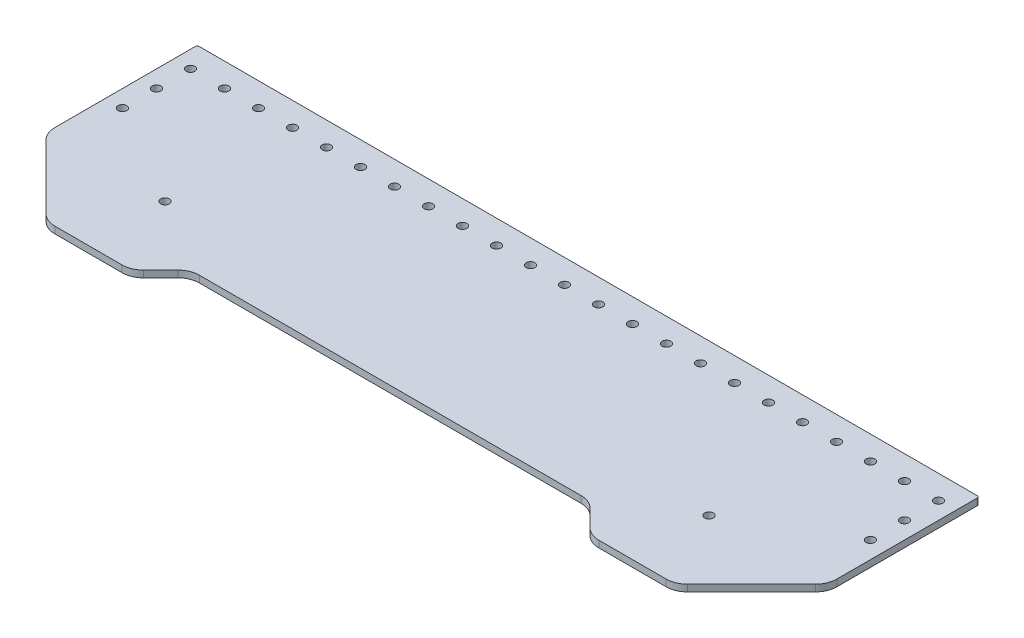
SolidWorks part; units mm, degrees
ref_plane "Front Plane" through (0, 0, 0) normal (0, 0, 1) x (1, 0, 0)
ref_plane "Top Plane" through (0, 0, 0) normal (0, 1, 0) x (1, 0, 0)
ref_plane "Right Plane" through (0, 0, 0) normal (1, 0, 0) x (0, 0, -1)
sketch "Sketch3" plane through (0, 0, 0) normal (0, 1, 0) x (1, 0, 0)
  line L0 (0, 0) -> (50000, 0) construction
  line L1 (184, -59.5875) -> (-184, -59.5875) construction
  line L2 (184, -59.5875) -> (184, 59.5875) construction
  line L3 (184, 59.5875) -> (-184, 59.5875) construction
  line L4 (-184, -59.5875) -> (-184, 59.5875) construction
  line L5 (184, -59.5875) -> (-184, 59.5875) construction
  line L6 (184, 59.5875) -> (-184, -59.5875) construction
  line L7 (0, 0) -> (0, -50000) construction
  line L8 (-141.9903, -11.5875) -> (49858.0097, -11.5875) construction
  line L9 (-130.2701, 7.3771) -> (-33.4655, 18.9646) construction
  line L10 (-128, -11.5875) -> (-31.1955, 0) construction
  line L11 (-125.7299, -30.5521) -> (-28.9254, -18.9646) construction
  line L12 (-49.1677, -33.5875) -> (49950.8323, -33.5875) construction
  line L13 (-47.419, -47.5875) -> (-50047.419, -47.5875) construction
  line L14 (-184, -11.5875) -> (-148, -47.5875)
  line L15 (-128, -11.5875) -> (-128, -50011.5875) construction
  line L16 (-148, -47.5875) -> (-108, -47.5875)
  line L17 (-94, -33.5875) -> (-108, -47.5875)
  line L18 (-94, -33.5875) -> (94, -33.5875)
  line L19 (-184, -11.5875) -> (-184, 59.5875)
  line L20 (-184, 59.5875) -> (184, 59.5875)
  line L21 (184, -11.5875) -> (184, 59.5875)
  line L22 (184, -11.5875) -> (148, -47.5875)
  line L23 (148, -47.5875) -> (108, -47.5875)
  line L24 (94, -33.5875) -> (108, -47.5875)
  line L26 (-15.1955, -16) -> (-47.1955, -16) construction
  line L27 (-15.1955, -16) -> (-15.1955, 16) construction
  line L28 (-15.1955, 16) -> (-47.1955, 16) construction
  line L29 (-47.1955, -16) -> (-47.1955, 16) construction
  line L30 (-15.1955, -16) -> (-47.1955, 16) construction
  line L31 (-15.1955, 16) -> (-47.1955, -16) construction
  line L32 (-9.1955, -22) -> (-53.1955, -22) construction
  line L33 (-9.1955, -22) -> (-9.1955, 22) construction
  line L34 (-9.1955, 22) -> (-53.1955, 22) construction
  line L35 (-53.1955, -22) -> (-53.1955, 22) construction
  line L36 (-9.1955, -22) -> (-53.1955, 22) construction
  line L37 (-9.1955, 22) -> (-53.1955, -22) construction
  circle A0 centre (-128, -11.5875) radius 48 construction
  circle A1 centre (-128, -11.5875) radius 19.1 construction
  circle A2 centre (-31.1955, 0) radius 19.1 construction
  arc A3 (-33.4655, 18.9646) -> (-28.9254, -18.9646) centre (-31.1955, 0) cw construction
  arc A4 (-130.2701, 7.3771) -> (-125.7299, -30.5521) centre (-128, -11.5875) ccw construction
  circle A5 centre (-128, -11.5875) radius 2.05
  circle A6 centre (-31.1955, 0) radius 2.05 construction
  circle A7 centre (128, -11.5875) radius 2.05
  circle A8 centre (31.1955, 0) radius 2.05 construction
  circle A9 centre (-53.1955, 22) radius 2.05 construction
  circle A10 centre (-53.1955, -22) radius 2.05 construction
  circle A11 centre (53.1955, 22) radius 2.05 construction
  circle A12 centre (53.1955, -22) radius 2.05 construction
  point P0 (0, 0)
  point P36 (0, 59.5875)
  point P40 (0, -33.5875)
  dimension "D4" = 96
  dimension "D6" = 38.2
  dimension "D12" = 4.1
  dimension "D1" = 368
  dimension "D2" = 119.175
  dimension "D3" = 48
  dimension "D5" = 56
  dimension "D8" = 26
  dimension "D9" = 12
  dimension "D10" = 45
  dimension "D11" = 45
  dimension "D13" = 32
  dimension "D14" = 44
extrude "Boss-Extrude2" add sketch "Sketch3" along normal blind 3.175
fillet "Fillet1" radius 10 8 edges at (184, 1.5875, 11.5875) (148, 1.5875, 47.5875) (108, 1.5875, 47.5875) (94, 1.5875, 33.5875) (-94, 1.5875, 33.5875) (-108, 1.5875, 47.5875) (-148, 1.5875, 47.5875) (-184, 1.5875, 11.5875)
fillet "Fillet2" radius 1 2 edges at (184, 1.5875, -59.5875) (-184, 1.5875, -59.5875)
sketch "Sketch5" plane through (0, 3.175, 0) normal (0, 1, 0) x (1, 0, 0)
  line L0 (0, 0) -> (0, -50000) construction
  circle A0 centre (-128, -11.5875) radius 48
  circle A1 centre (128, -11.5875) radius 48
  dimension "D1" = 96
sketch "Sketch6" plane through (0, 3.175, 0) normal (0, 1, 0) x (1, 0, 0)
  line L0 (0, 0) -> (0, -50000) construction
  line L2 (0, 0) -> (50000, 0) construction
  line L3 (21.2444, 56.4125) -> (50021.2444, 56.4125) construction
  line L4 (21.9898, 48.4125) -> (50021.9898, 48.4125) construction
  line L5 (183, 59.5875) -> (-183, 59.5875) construction
  line L6 (-176, 42.191) -> (-176, -49957.809) construction
  line L7 (-184, 58.5875) -> (-184, -7.4454) construction
  line L8 (-176, 48.4125) -> (-160, 48.4125) construction
  line L9 (-176, 48.4125) -> (-176.014, 32.4125) construction
  circle A0 centre (-176, 48.4125) radius 2.05
  circle A1 centre (-160, 48.4125) radius 2.05
  circle A2 centre (-144, 48.4125) radius 2.05
  circle A3 centre (-128, 48.4125) radius 2.05
  circle A4 centre (-112, 48.4125) radius 2.05
  circle A5 centre (-96, 48.4125) radius 2.05
  circle A6 centre (-80, 48.4125) radius 2.05
  circle A7 centre (-64, 48.4125) radius 2.05
  circle A8 centre (-48, 48.4125) radius 2.05
  circle A9 centre (-32, 48.4125) radius 2.05
  circle A10 centre (-16, 48.4125) radius 2.05
  circle A11 centre (0, 48.4125) radius 2.05
  circle A12 centre (16, 48.4125) radius 2.05
  circle A13 centre (32, 48.4125) radius 2.05
  circle A14 centre (48, 48.4125) radius 2.05
  circle A15 centre (64, 48.4125) radius 2.05
  circle A16 centre (80, 48.4125) radius 2.05
  circle A17 centre (96, 48.4125) radius 2.05
  circle A18 centre (112, 48.4125) radius 2.05
  circle A19 centre (128, 48.4125) radius 2.05
  circle A20 centre (144, 48.4125) radius 2.05
  circle A21 centre (160, 48.4125) radius 2.05
  circle A22 centre (176, 48.4125) radius 2.05
  circle A23 centre (-160.014, 32.4125) radius 2.05 construction
  circle A24 centre (-144.014, 32.4125) radius 2.05 construction
  circle A25 centre (-128.014, 32.4125) radius 2.05 construction
  circle A26 centre (-112.014, 32.4125) radius 2.05 construction
  circle A27 centre (-96.014, 32.4125) radius 2.05 construction
  circle A28 centre (-80.014, 32.4125) radius 2.05 construction
  circle A29 centre (-64.014, 32.4125) radius 2.05 construction
  circle A30 centre (-48.014, 32.4125) radius 2.05 construction
  circle A31 centre (-32.014, 32.4125) radius 2.05 construction
  circle A32 centre (-16.014, 32.4125) radius 2.05 construction
  circle A33 centre (-0.014, 32.4125) radius 2.05 construction
  circle A34 centre (15.986, 32.4125) radius 2.05 construction
  circle A35 centre (31.986, 32.4125) radius 2.05 construction
  circle A36 centre (47.986, 32.4125) radius 2.05 construction
  circle A37 centre (63.986, 32.4125) radius 2.05 construction
  circle A38 centre (79.986, 32.4125) radius 2.05 construction
  circle A39 centre (95.986, 32.4125) radius 2.05 construction
  circle A40 centre (111.986, 32.4125) radius 2.05 construction
  circle A41 centre (127.986, 32.4125) radius 2.05 construction
  circle A42 centre (143.986, 32.4125) radius 2.05 construction
  circle A43 centre (159.986, 32.4125) radius 2.05 construction
  circle A44 centre (175.986, 32.4125) radius 2.05
  circle A45 centre (-160.028, 16.4125) radius 2.05 construction
  circle A46 centre (-144.028, 16.4125) radius 2.05 construction
  circle A47 centre (-128.028, 16.4125) radius 2.05 construction
  circle A48 centre (-112.028, 16.4125) radius 2.05 construction
  circle A49 centre (-96.028, 16.4125) radius 2.05 construction
  circle A50 centre (-80.028, 16.4125) radius 2.05 construction
  circle A51 centre (-64.028, 16.4125) radius 2.05 construction
  circle A52 centre (-48.028, 16.4125) radius 2.05 construction
  circle A53 centre (-32.028, 16.4125) radius 2.05 construction
  circle A54 centre (-16.028, 16.4125) radius 2.05 construction
  circle A55 centre (-0.028, 16.4125) radius 2.05 construction
  circle A56 centre (15.972, 16.4125) radius 2.05 construction
  circle A57 centre (31.972, 16.4125) radius 2.05 construction
  circle A58 centre (47.972, 16.4125) radius 2.05 construction
  circle A59 centre (63.972, 16.4125) radius 2.05 construction
  circle A60 centre (79.972, 16.4125) radius 2.05 construction
  circle A61 centre (95.972, 16.4125) radius 2.05 construction
  circle A62 centre (111.972, 16.4125) radius 2.05 construction
  circle A63 centre (127.972, 16.4125) radius 2.05 construction
  circle A64 centre (143.972, 16.4125) radius 2.05 construction
  circle A65 centre (159.972, 16.4125) radius 2.05 construction
  circle A66 centre (175.972, 16.4125) radius 2.05
  circle A67 centre (-160.042, 0.4125) radius 2.05 construction
  circle A68 centre (-144.042, 0.4125) radius 2.05 construction
  circle A69 centre (-128.042, 0.4125) radius 2.05 construction
  circle A70 centre (-112.042, 0.4125) radius 2.05 construction
  circle A71 centre (-96.042, 0.4125) radius 2.05 construction
  circle A72 centre (-80.042, 0.4125) radius 2.05 construction
  circle A73 centre (-64.042, 0.4125) radius 2.05 construction
  circle A74 centre (-48.042, 0.4125) radius 2.05 construction
  circle A75 centre (-32.042, 0.4125) radius 2.05 construction
  circle A76 centre (-16.042, 0.4125) radius 2.05 construction
  circle A77 centre (-0.042, 0.4125) radius 2.05 construction
  circle A78 centre (15.958, 0.4125) radius 2.05 construction
  circle A79 centre (31.958, 0.4125) radius 2.05 construction
  circle A80 centre (47.958, 0.4125) radius 2.05 construction
  circle A81 centre (63.958, 0.4125) radius 2.05 construction
  circle A82 centre (79.958, 0.4125) radius 2.05 construction
  circle A83 centre (95.958, 0.4125) radius 2.05 construction
  circle A84 centre (111.958, 0.4125) radius 2.05 construction
  circle A85 centre (127.958, 0.4125) radius 2.05 construction
  circle A86 centre (143.958, 0.4125) radius 2.05 construction
  circle A87 centre (159.958, 0.4125) radius 2.05 construction
  circle A88 centre (175.958, 0.4125) radius 2.05 construction
  circle A89 centre (-160.056, -15.5875) radius 2.05 construction
  circle A90 centre (-144.056, -15.5875) radius 2.05 construction
  circle A91 centre (-128.056, -15.5875) radius 2.05 construction
  circle A92 centre (-112.056, -15.5875) radius 2.05 construction
  circle A93 centre (-96.056, -15.5875) radius 2.05 construction
  circle A94 centre (-80.056, -15.5875) radius 2.05 construction
  circle A95 centre (-64.056, -15.5875) radius 2.05 construction
  circle A96 centre (-48.056, -15.5875) radius 2.05 construction
  circle A97 centre (-32.056, -15.5875) radius 2.05 construction
  circle A98 centre (-16.056, -15.5875) radius 2.05 construction
  circle A99 centre (-0.056, -15.5875) radius 2.05 construction
  circle A100 centre (15.944, -15.5875) radius 2.05 construction
  circle A101 centre (31.944, -15.5875) radius 2.05 construction
  circle A102 centre (47.944, -15.5875) radius 2.05 construction
  circle A103 centre (63.944, -15.5875) radius 2.05 construction
  circle A104 centre (79.944, -15.5875) radius 2.05 construction
  circle A105 centre (95.944, -15.5875) radius 2.05 construction
  circle A106 centre (111.944, -15.5875) radius 2.05 construction
  circle A107 centre (127.944, -15.5875) radius 2.05 construction
  circle A108 centre (143.944, -15.5875) radius 2.05 construction
  circle A109 centre (159.944, -15.5875) radius 2.05 construction
  circle A110 centre (175.944, -15.5875) radius 2.05 construction
  circle A111 centre (-160.0699, -31.5875) radius 2.05 construction
  circle A112 centre (-144.0699, -31.5875) radius 2.05 construction
  circle A113 centre (-128.0699, -31.5875) radius 2.05 construction
  circle A114 centre (-112.0699, -31.5875) radius 2.05 construction
  circle A115 centre (-96.0699, -31.5875) radius 2.05 construction
  circle A116 centre (-80.0699, -31.5875) radius 2.05 construction
  circle A117 centre (-64.0699, -31.5875) radius 2.05 construction
  circle A118 centre (-48.0699, -31.5875) radius 2.05 construction
  circle A119 centre (-32.0699, -31.5875) radius 2.05 construction
  circle A120 centre (-16.0699, -31.5875) radius 2.05 construction
  circle A121 centre (-0.0699, -31.5875) radius 2.05 construction
  circle A122 centre (15.9301, -31.5875) radius 2.05 construction
  circle A123 centre (31.9301, -31.5875) radius 2.05 construction
  circle A124 centre (47.9301, -31.5875) radius 2.05 construction
  circle A125 centre (63.9301, -31.5875) radius 2.05 construction
  circle A126 centre (79.9301, -31.5875) radius 2.05 construction
  circle A127 centre (95.9301, -31.5875) radius 2.05 construction
  circle A128 centre (111.9301, -31.5875) radius 2.05 construction
  circle A129 centre (127.9301, -31.5875) radius 2.05 construction
  circle A130 centre (143.9301, -31.5875) radius 2.05 construction
  circle A131 centre (159.9301, -31.5875) radius 2.05 construction
  circle A132 centre (175.9301, -31.5875) radius 2.05 construction
  circle A133 centre (-160.0839, -47.5875) radius 2.05 construction
  circle A134 centre (-144.0839, -47.5875) radius 2.05 construction
  circle A135 centre (-128.0839, -47.5875) radius 2.05 construction
  circle A136 centre (-112.0839, -47.5875) radius 2.05 construction
  circle A137 centre (-96.0839, -47.5875) radius 2.05 construction
  circle A138 centre (-80.0839, -47.5875) radius 2.05 construction
  circle A139 centre (-64.0839, -47.5875) radius 2.05 construction
  circle A140 centre (-48.0839, -47.5875) radius 2.05 construction
  circle A141 centre (-32.0839, -47.5875) radius 2.05 construction
  circle A142 centre (-16.0839, -47.5875) radius 2.05 construction
  circle A143 centre (-0.0839, -47.5875) radius 2.05 construction
  circle A144 centre (15.9161, -47.5875) radius 2.05 construction
  circle A145 centre (31.9161, -47.5875) radius 2.05 construction
  circle A146 centre (47.9161, -47.5875) radius 2.05 construction
  circle A147 centre (63.9161, -47.5875) radius 2.05 construction
  circle A148 centre (79.9161, -47.5875) radius 2.05 construction
  circle A149 centre (95.9161, -47.5875) radius 2.05 construction
  circle A150 centre (111.9161, -47.5875) radius 2.05 construction
  circle A151 centre (127.9161, -47.5875) radius 2.05 construction
  circle A152 centre (143.9161, -47.5875) radius 2.05 construction
  circle A153 centre (159.9161, -47.5875) radius 2.05 construction
  circle A154 centre (175.9161, -47.5875) radius 2.05 construction
  circle A155 centre (-176.014, 32.4125) radius 2.05
  circle A156 centre (-176.028, 16.4125) radius 2.05
  circle A157 centre (-176.042, 0.4125) radius 2.05 construction
  circle A158 centre (-176.056, -15.5875) radius 2.05 construction
  circle A159 centre (-176.0699, -31.5875) radius 2.05 construction
  circle A160 centre (-176.0839, -47.5875) radius 2.05 construction
  dimension "D4" = 4.1
  dimension "D1" = 8
  dimension "D2" = 3.175
  dimension "D3" = 8
  dimension "D7" = 16
  dimension "D8" = 16
  dimension "D5" = 23
  dimension "D6" = 7
extrude "Cut-Extrude3" cut sketch "Sketch6" against normal blind 3.18
equation "\"wheelDiameter\"= 96mm"
equation "\"thick\"= 3.175mm"
equation "\"sh\"= 4.1mm"
equation "\"w\"= 368mm"
equation "\"h\"= \"wheelDiameter\" + 20mm + 3.175mm"
equation "\"pitchDiameter\"= 38.2mm"
equation "\"D1@Sketch3\"=\"w\""
equation "\"D2@Sketch3\"=\"h\""
equation "\"D3@Sketch3\"=\"wheelDiameter\"/2"
equation "\"D4@Sketch3\"=\"wheelDiameter\""
equation "\"D5@Sketch3\"=\"wheelDiameter\"/2 +8"
equation "\"D6@Sketch3\"=\"pitchDiameter\""
equation "\"beltPitch\"= 315mm"
equation "\"D7@Sketch3\"=\"beltPitch\""
equation "\"D12@Sketch3\"=\"sh\""
equation "\"D1@Boss-Extrude2\"=\"thick\""
equation "\"D1@Sketch5\"=\"wheelDiameter\""
equation "\"D2@Sketch6\"=\"thick\""
equation "\"D4@Sketch6\"=\"sh\""
equation "\"strut\"= 8mm"
